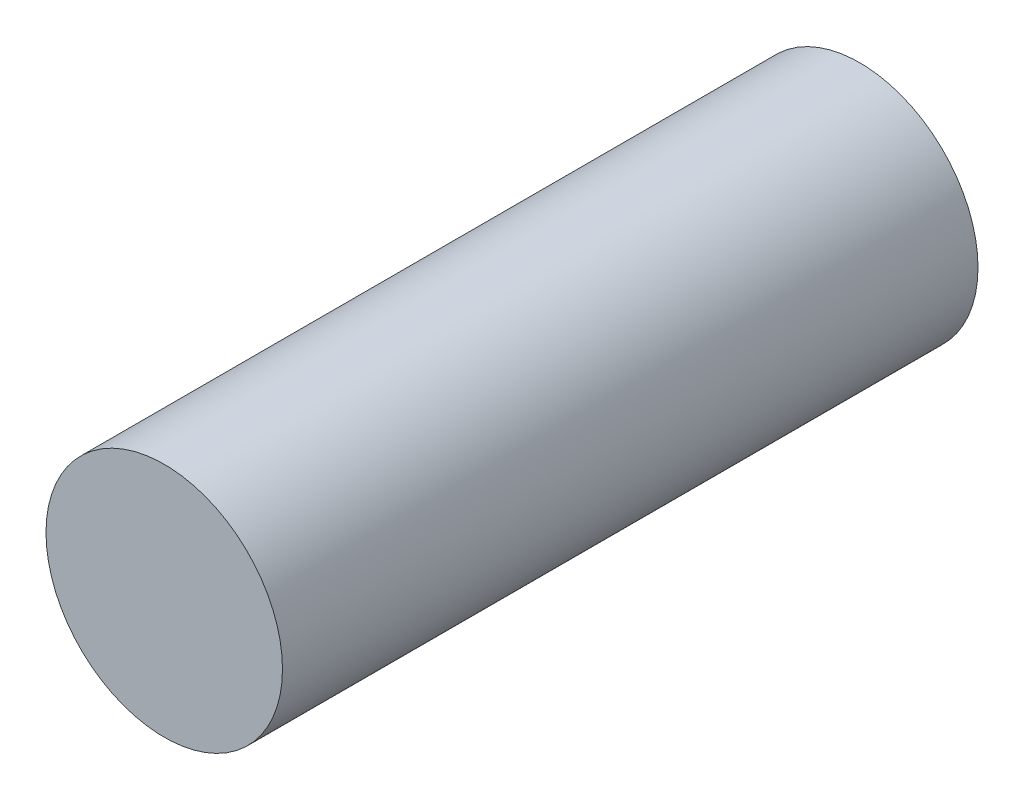
SolidWorks part; units mm, degrees
ref_plane "前视" through (0, 0, 0) normal (0, 0, 1) x (1, 0, 0)
ref_plane "上视" through (0, 0, 0) normal (0, 1, 0) x (1, 0, 0)
ref_plane "右视" through (0, 0, 0) normal (1, 0, 0) x (0, 0, -1)
sketch "草图1" plane through (0, 0, 0) normal (0, 0, 1) x (1, 0, 0)
  circle A0 centre (0, 0) radius 17
extrude "凸台-拉伸1" add sketch "草图1" along normal blind 100 contours A0
